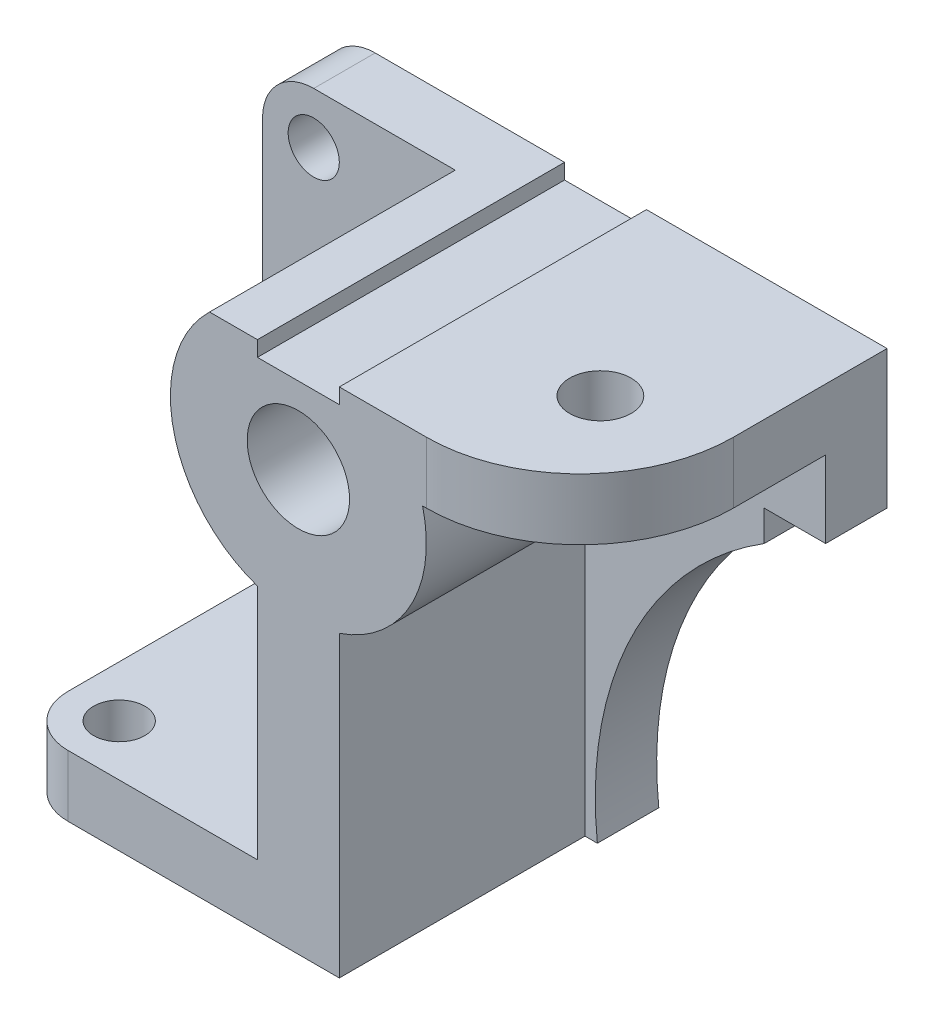
SolidWorks part; units mm, degrees
ref_plane "Front Plane" through (0, 0, 0) normal (0, 0, 1) x (1, 0, 0)
ref_plane "Top Plane" through (0, 0, 0) normal (0, 1, 0) x (1, 0, 0)
ref_plane "Right Plane" through (0, 0, 0) normal (1, 0, 0) x (0, 0, -1)
sketch "Sketch1" plane through (0, 0, 0) normal (0, 0, 1) x (1, 0, 0)
  line L1 (-55, 50) -> (55, 50)
  line L2 (-55, 50) -> (-55, -50)
  line L3 (-55, -50) -> (55, -50)
  line L4 (55, 50) -> (55, -50)
  line L5 (-55, 50) -> (55, -50) construction
  line L6 (-55, -50) -> (55, 50) construction
  point P0 (0, 0)
  dimension "D1" = 110
  dimension "D2" = 100
extrude "Boss-Extrude1" add sketch "Sketch1" along normal mid plane 60
sketch "Sketch2" plane through (0, 0, 30) normal (0, 0, 1) x (1, 0, 0)
  line L0 (0, 50) -> (0, -56.0647) construction
  line L1 (55, 50) -> (-55, 50) construction
  line L2 (-55, -50) -> (55, -50) construction
  line L10 (-8, 8.3146) -> (-8, -38)
  line L16 (-17.3494, 50) -> (-55, 50)
  line L17 (-55, 50) -> (-55, -38)
  line L19 (-8, -38) -> (-55, -38)
  arc A0 (-17.3494, 50) -> (-8, 8.3146) centre (0, 32) ccw
  dimension "D1" = 50
  dimension "D2" = 18
  dimension "D3" = 8
  dimension "D4" = 12
extrude "Cut-Extrude1" cut sketch "Sketch2" against normal blind 48
sketch "Sketch3" plane through (0, 0, 30) normal (0, 0, 1) x (1, 0, 0)
  line L1 (55, -50) -> (55, 50) construction
  line L5 (43, 23) -> (55, 23)
  line L6 (43, 23) -> (43, 17)
  line L7 (43, 17) -> (55, 17)
  line L8 (55, 23) -> (55, 17)
  line L9 (43, 23) -> (55, 17) construction
  line L10 (43, 17) -> (55, 23) construction
  line L11 (55, 50) -> (-17.3494, 50) construction
  point P0 (49, 20)
  dimension "D1" = 6
  dimension "D2" = 12
  dimension "D3" = 27
extrude "Cut-Extrude2" cut sketch "Sketch3" against normal through all contours L5 L8 L7 L6
sketch "Sketch4" plane through (0, 0, 30) normal (0, 0, 1) x (1, 0, 0)
  line L0 (-55, -50) -> (55, -50) construction
  line L1 (43, 23) -> (43, 17) construction
  line L2 (0, 0) -> (0, -60.4262) construction
  line L3 (43, 23) -> (55, 23) construction
  line L4 (55, 23) -> (55, 50) construction
  line L6 (8, -50) -> (10.4114, -50)
  line L7 (43, 23) -> (43, 17)
  line L8 (43, 23) -> (55, 23)
  line L9 (55, 23) -> (55, 38)
  line L11 (8, 8.3146) -> (8, -50)
  line L12 (-8, -38) -> (-8, 8.3146) construction
  line L13 (24.2693, 38) -> (55, 38)
  line L14 (55, 50) -> (-17.3494, 50) construction
  arc A0 (43, 17) -> (10.4114, -50) centre (80, -42.4222) ccw
  arc A1 (8, 8.3146) -> (24.2693, 38) centre (0, 32) ccw
  point P1 (0, 0)
  dimension "D1" = 12
  dimension "D2" = 140
  dimension "D3" = 80
extrude "Cut-Extrude5" cut sketch "Sketch4" against normal blind 48
sketch "Sketch6" plane through (0, 0, 30) normal (0, 0, 1) x (1, 0, 0)
  line L0 (55, -50) -> (55, 17) construction
  line L1 (10.4114, -50) -> (55, -50) construction
  line L2 (43, 17) -> (55, 17) construction
  line L3 (55, -50) -> (55, 17)
  line L4 (10.4114, -50) -> (55, -50)
  line L5 (43, 17) -> (55, 17)
  arc A0 (43, 17) -> (10.4114, -50) centre (80, -42.4222) ccw construction
  arc A1 (43, 17) -> (10.4114, -50) centre (80, -42.4222) ccw
extrude "Cut-Extrude6" cut sketch "Sketch6" against normal through all
hole_wizard "Hole1" positions "Sketch7" profile "Sketch8" legacy end condition up to next
sketch "Sketch7" plane through (0, 0, 30) normal (0, 0, 1) x (1, 0, 0)
  point P0 (0, 32)
sketch "Sketch8" plane through (0, 32, 30) normal (1, 0, 0) x (0, -1, 0)
  line L0 (0, 0) -> (0, 60)
  line L1 (0, 60) -> (10, 60)
  line L2 (10, 60) -> (10, 0)
  line L3 (10, 0) -> (0, 0)
  line L4 (0, 110) -> (0, -10) construction
  dimension "Diameter" = 20
  dimension "Depth" = 60
fillet "Fillet1" radius 10 2 edges at (-55, 50, -24) (-55, -44, 30)
fillet "Fillet2" radius 30 1 edges at (55, 44, 30)
hole_wizard "Hole2" positions "Sketch9" profile "Sketch10" legacy end condition up to next
sketch "Sketch9" plane through (0, 50, 0) normal (0, 1, 0) x (1, 0, 0)
  line L0 (55, 0) -> (55, 30) construction
  line L1 (25, -30) -> (-17.3494, -30) construction
  point P0 (35, -6)
  dimension "D1" = 20
  dimension "D2" = 24
sketch "Sketch10" plane through (35, 50, 6) normal (1, 0, 0) x (0, 0, 1)
  line L0 (0, 0) -> (0, 12)
  line L1 (0, 12) -> (6, 12)
  line L2 (6, 12) -> (6, 0)
  line L3 (6, 0) -> (0, 0)
  line L4 (0, 110) -> (0, -10) construction
  dimension "Diameter" = 12
  dimension "Depth" = 12
hole_wizard "Hole3" positions "Sketch11" profile "Sketch12" legacy end condition up to next
sketch "Sketch11" plane through (0, -38, 0) normal (0, 1, 0) x (1, 0, 0)
  point P0 (-45, -20)
sketch "Sketch12" plane through (-45, -38, 20) normal (1, 0, 0) x (0, 0, 1)
  line L0 (0, 0) -> (0, 12)
  line L1 (0, 12) -> (5, 12)
  line L2 (5, 12) -> (5, 0)
  line L3 (5, 0) -> (0, 0)
  line L4 (0, 110) -> (0, -10) construction
  dimension "Diameter" = 10
  dimension "Depth" = 12
hole_wizard "Hole4" positions "Sketch13" profile "Sketch14" legacy end condition up to next
sketch "Sketch13" plane through (0, 0, -18) normal (0, 0, 1) x (1, 0, 0)
  point P0 (-45, 40)
sketch "Sketch14" plane through (-45, 40, -18) normal (1, 0, 0) x (0, -1, 0)
  line L0 (0, 0) -> (0, 12)
  line L1 (0, 12) -> (5, 12)
  line L2 (5, 12) -> (5, 0)
  line L3 (5, 0) -> (0, 0)
  line L4 (0, 110) -> (0, -10) construction
  dimension "Diameter" = 10
  dimension "Depth" = 12
sketch "Sketch15" plane through (0, 0, 30) normal (0, 0, 1) x (1, 0, 0)
  line L0 (25, 50) -> (-17.3494, 50) construction
  line L1 (-8, 47) -> (8, 47)
  line L2 (-8, 47) -> (-8, 50)
  line L3 (-8, 50) -> (8, 50)
  line L4 (8, 47) -> (8, 50)
  line L5 (-8, 47) -> (8, 50) construction
  line L6 (-8, 50) -> (8, 47) construction
  point P0 (0, 48.5)
  dimension "D1" = 3
  dimension "D2" = 16
extrude "Cut-Extrude7" cut sketch "Sketch15" against normal through all
